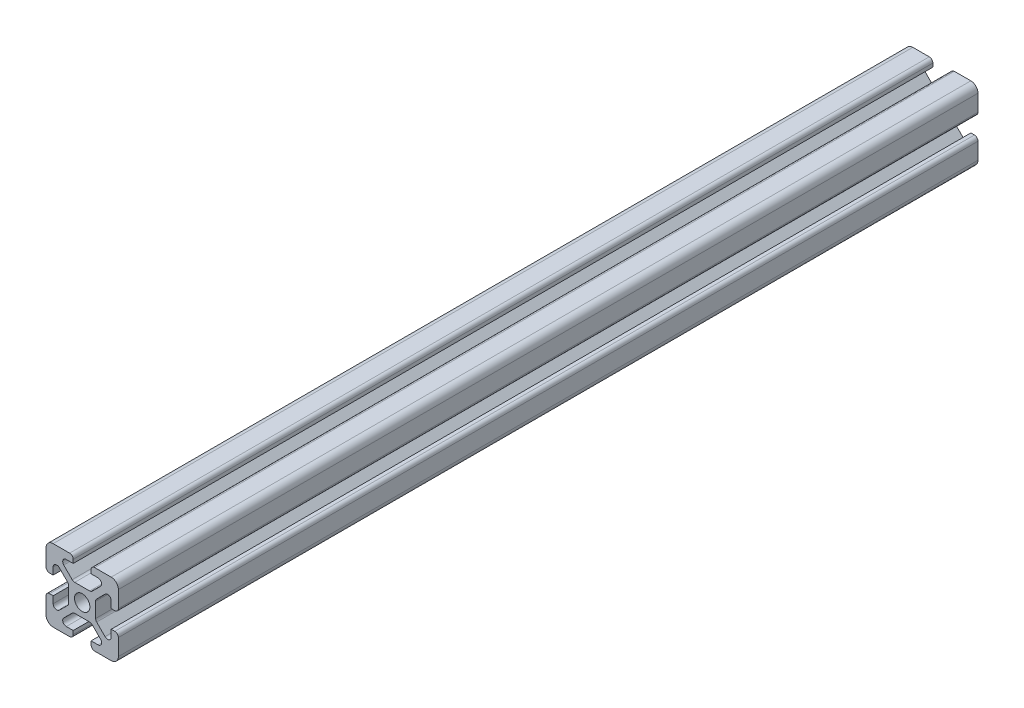
SolidWorks part; units mm, degrees
ref_plane "Front Plane" through (0, 0, 0) normal (0, 0, 1) x (1, 0, 0)
ref_plane "Top Plane" through (0, 0, 0) normal (0, 1, 0) x (1, 0, 0)
ref_plane "Right Plane" through (0, 0, 0) normal (1, 0, 0) x (0, 0, -1)
sketch "Sketch1" plane through (0, 0, 0) normal (0, 0, 1) x (1, 0, 0)
  line L0 (10.1, 10) -> (10.1, 0.1) construction
  line L1 (2, 0) -> (6.6, 0)
  line L2 (0, 2) -> (0, 6.6)
  line L3 (2, 20.2) -> (6.6, 20.2)
  line L4 (20.2, 2) -> (20.2, 6.6)
  line L5 (10.1, 10) -> (0, 10) construction
  line L6 (7.6, 19.2) -> (7.6, 18.2)
  line L7 (7.6, 18.2) -> (5.6642, 18.2)
  line L8 (4.9571, 16.4929) -> (7.3071, 14.1429)
  line L9 (8.0142, 13.85) -> (12.1858, 13.85)
  line L10 (12.8929, 14.1429) -> (15.2429, 16.4929)
  line L11 (14.5358, 18.2) -> (12.6, 18.2)
  line L12 (12.6, 18.2) -> (12.6, 19.2)
  line L13 (-250.157, -110.88) -> (53.1764, -110.88) construction
  line L14 (13.6, 20.2) -> (18.2, 20.2)
  line L15 (19.2, 12.6) -> (18.2, 12.6)
  line L16 (18.2, 12.6) -> (18.2, 14.5358)
  line L17 (16.4929, 15.2429) -> (14.1429, 12.8929)
  line L18 (13.85, 12.1858) -> (13.85, 8.0142)
  line L19 (14.1429, 7.3071) -> (16.4929, 4.9571)
  line L20 (18.2, 5.6642) -> (18.2, 7.6)
  line L21 (18.2, 7.6) -> (19.2, 7.6)
  line L22 (12.6, 1) -> (12.6, 2)
  line L23 (12.6, 2) -> (14.5358, 2)
  line L24 (15.2429, 3.7071) -> (12.8929, 6.0571)
  line L25 (12.1858, 6.35) -> (8.0142, 6.35)
  line L26 (7.3071, 6.0571) -> (4.9571, 3.7071)
  line L27 (5.6642, 2) -> (7.6, 2)
  line L28 (7.6, 2) -> (7.6, 1)
  line L29 (1, 7.6) -> (2, 7.6)
  line L30 (2, 7.6) -> (2, 5.6642)
  line L31 (3.7071, 4.9571) -> (6.0571, 7.3071)
  line L32 (6.35, 8.0142) -> (6.35, 12.1858)
  line L33 (6.0571, 12.8929) -> (3.7071, 15.2429)
  line L34 (2, 14.5358) -> (2, 12.6)
  line L35 (2, 12.6) -> (1, 12.6)
  line L36 (20.2, 13.6) -> (20.2, 18.2)
  line L37 (13.6, 0) -> (18.2, 0)
  line L38 (0, 13.6) -> (0, 18.2)
  circle A0 centre (10.1, 10) radius 2.15
  arc A1 (12.8929, 14.1429) -> (12.1858, 13.85) centre (12.1858, 14.85) cw
  arc A2 (8.0142, 13.85) -> (7.3071, 14.1429) centre (8.0142, 14.85) cw
  arc A3 (15.2429, 16.4929) -> (14.5358, 18.2) centre (14.5358, 17.2) ccw
  arc A4 (5.6642, 18.2) -> (4.9571, 16.4929) centre (5.6642, 17.2) ccw
  arc A5 (2, 0) -> (0, 2) centre (2, 2) cw
  arc A6 (18.2, 0) -> (20.2, 2) centre (18.2, 2) ccw
  arc A7 (20.2, 18.2) -> (18.2, 20.2) centre (18.2, 18.2) ccw
  arc A8 (2, 20.2) -> (0, 18.2) centre (2, 18.2) ccw
  arc A9 (18.2, 14.5358) -> (16.4929, 15.2429) centre (17.2, 14.5358) ccw
  arc A10 (13.85, 12.1858) -> (14.1429, 12.8929) centre (14.85, 12.1858) cw
  arc A11 (14.1429, 7.3071) -> (13.85, 8.0142) centre (14.85, 8.0142) cw
  arc A12 (16.4929, 4.9571) -> (18.2, 5.6642) centre (17.2, 5.6642) ccw
  arc A13 (14.5358, 2) -> (15.2429, 3.7071) centre (14.5358, 3) ccw
  arc A14 (12.1858, 6.35) -> (12.8929, 6.0571) centre (12.1858, 5.35) cw
  arc A15 (7.3071, 6.0571) -> (8.0142, 6.35) centre (8.0142, 5.35) cw
  arc A16 (4.9571, 3.7071) -> (5.6642, 2) centre (5.6642, 3) ccw
  arc A17 (2, 5.6642) -> (3.7071, 4.9571) centre (3, 5.6642) ccw
  arc A18 (6.35, 8.0142) -> (6.0571, 7.3071) centre (5.35, 8.0142) cw
  arc A19 (6.0571, 12.8929) -> (6.35, 12.1858) centre (5.35, 12.1858) cw
  arc A20 (3.7071, 15.2429) -> (2, 14.5358) centre (3, 14.5358) ccw
  arc A21 (20.2, 13.6) -> (19.2, 12.6) centre (19.2, 13.6) cw
  arc A22 (20.2, 6.6) -> (19.2, 7.6) centre (19.2, 6.6) ccw
  arc A23 (13.6, 0) -> (12.6, 1) centre (13.6, 1) cw
  arc A24 (7.6, 1) -> (6.6, 0) centre (6.6, 1) cw
  arc A25 (1, 7.6) -> (0, 6.6) centre (1, 6.6) ccw
  arc A26 (1, 12.6) -> (0, 13.6) centre (1, 13.6) cw
  arc A27 (7.6, 19.2) -> (6.6, 20.2) centre (6.6, 19.2) ccw
  arc A28 (13.6, 20.2) -> (12.6, 19.2) centre (13.6, 19.2) ccw
  point P21 (12.6, 13.85)
  point P24 (7.6, 13.85)
  point P31 (0, 0)
  point P36 (20.2, 20.2)
  point P39 (0, 20.2)
  point P91 (10.1, 10.1)
  point P105 (12.6, 20.2)
  dimension "D3" = 4.3
  dimension "D9" = 1
  dimension "D10" = 2
  dimension "D13" = 1
  dimension "D1" = 20.2
  dimension "D2" = 10.1
  dimension "D4" = 5
  dimension "D5" = 2.5
  dimension "D6" = 6.35
  dimension "D7" = 2
  dimension "D8" = 45
  dimension "D12" = 10
  dimension "D14" = 20.2
  dimension "D15" = 7.6
  dimension "D16" = 6.35
  dimension "D11" = 4
extrude "Boss-Extrude1" add sketch "Sketch1" along normal blind 240
